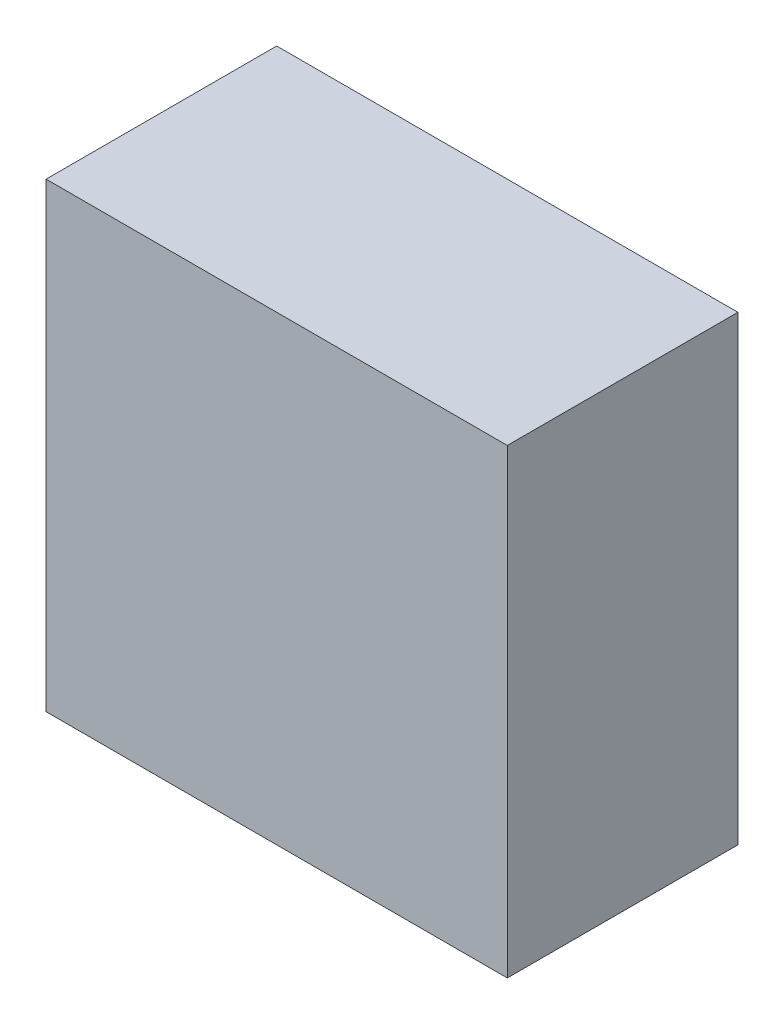
SolidWorks part; units mm, degrees
ref_plane "Front Plane" through (0, 0, 0) normal (0, 0, 1) x (1, 0, 0)
ref_plane "Top Plane" through (0, 0, 0) normal (0, 1, 0) x (1, 0, 0)
ref_plane "Right Plane" through (0, 0, 0) normal (1, 0, 0) x (0, 0, -1)
sketch "Sketch1" plane through (0, 0, 0) normal (0, 0, 1) x (1, 0, 0)
  line L0 (1, -1) -> (-1, -1)
  line L1 (-1, -1) -> (-1, 1)
  line L2 (-1, 1) -> (1, 1)
  line L3 (1, 1) -> (1, -1)
extrude "Component_Outline" add sketch "Sketch1" along normal blind 1 separate body
sketch3d "3DSketch1"
  line L0 (0, 0, 0) -> (1, 0, 0)
  line L1 (0, 0, 0) -> (0, 1, 0)
  line L2 (0, 0, 0) -> (0, 0, 1)
  point P0 (0, 0, 0)
